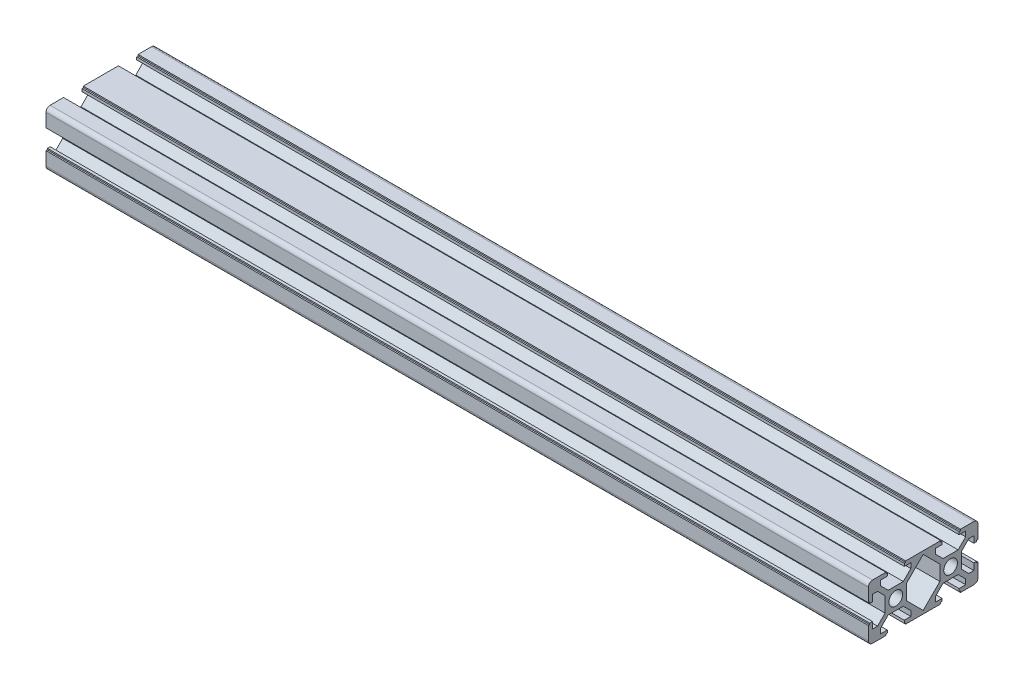
SolidWorks part; units mm, degrees
ref_plane "前视基准面" through (0, 0, 0) normal (0, 0, 1) x (1, 0, 0)
ref_plane "上视基准面" through (0, 0, 0) normal (0, 1, 0) x (1, 0, 0)
ref_plane "右视基准面" through (0, 0, 0) normal (1, 0, 0) x (0, 0, -1)
sketch "草图1" plane through (0, 0, 0) normal (0, 0, 1) x (1, 0, 0)
  line L0 (-53.3425, -1.4522) -> (246.6575, -1.4522)
other "铝型材 20X40XR1.5(2)"
ref_plane "基准面9" through (-53.3425, -1.4522, 0) normal (1, 0, 0) x (0, 1, 0)
sketch "Sketch16" plane through (-53.3425, -1.4522, 0) normal (1, 0, 0) x (0, 1, 0)
  line L0 (-3.6, 10) -> (-3.6, 9.5)
  line L1 (-3.6, 9.5) -> (-3.1, 9.5)
  line L2 (-3.1, 9.5) -> (-3.1, 8.5)
  line L3 (-3.1, 8.5) -> (-5.5, 8.5)
  line L4 (8.85, -10) -> (2.75, -3.9)
  line L5 (-10, -16.4) -> (-10, -3.6)
  line L6 (8.5, 10) -> (3.6, 10)
  line L7 (10, 8.5) -> (10, 3.6)
  line L8 (0, 14.8756) -> (0, 0) construction
  line L9 (0, 0) -> (10, 0) construction
  line L10 (-5.5, 8.5) -> (-5.5, 6.65)
  line L11 (-5.5, 6.65) -> (-2.75, 3.9)
  line L12 (-2.75, 3.9) -> (2.75, 3.9)
  line L13 (5.5, 6.65) -> (2.75, 3.9)
  line L14 (5.5, 8.5) -> (5.5, 6.65)
  line L15 (3.1, 8.5) -> (5.5, 8.5)
  line L16 (3.1, 9.5) -> (3.1, 8.5)
  line L17 (3.6, 9.5) -> (3.1, 9.5)
  line L18 (3.6, 10) -> (3.6, 9.5)
  line L19 (-3.6, 10) -> (-8.5, 10)
  line L20 (10, 3.6) -> (9.5, 3.6)
  line L21 (9.5, 3.6) -> (9.5, 3.1)
  line L22 (9.5, 3.1) -> (8.5, 3.1)
  line L23 (8.5, 3.1) -> (8.5, 5.5)
  line L24 (8.5, 5.5) -> (6.65, 5.5)
  line L25 (6.65, 5.5) -> (3.9, 2.75)
  line L26 (3.9, 2.75) -> (3.9, -2.75)
  line L27 (6.65, -5.5) -> (3.9, -2.75)
  line L28 (8.5, -5.5) -> (6.65, -5.5)
  line L29 (8.5, -3.1) -> (8.5, -5.5)
  line L30 (9.5, -3.1) -> (8.5, -3.1)
  line L31 (9.5, -3.6) -> (9.5, -3.1)
  line L32 (10, -3.6) -> (9.5, -3.6)
  line L33 (8.85, -10) -> (2.75, -16.1)
  line L34 (-8.85, -10) -> (-2.75, -16.1)
  line L35 (-8.85, -10) -> (-2.75, -3.9)
  line L39 (2.75, -3.9) -> (-2.75, -3.9)
  line L46 (-10, -3.6) -> (-9.5, -3.6)
  line L47 (-9.5, -3.6) -> (-9.5, -3.1)
  line L48 (-9.5, -3.1) -> (-8.5, -3.1)
  line L49 (-8.5, -3.1) -> (-8.5, -5.5)
  line L50 (-8.5, -5.5) -> (-6.65, -5.5)
  line L51 (-6.65, -5.5) -> (-3.9, -2.75)
  line L52 (-3.9, -2.75) -> (-3.9, 2.75)
  line L53 (-6.65, 5.5) -> (-3.9, 2.75)
  line L54 (-8.5, 5.5) -> (-6.65, 5.5)
  line L55 (-8.5, 3.1) -> (-8.5, 5.5)
  line L56 (-9.5, 3.1) -> (-8.5, 3.1)
  line L57 (-9.5, 3.6) -> (-9.5, 3.1)
  line L58 (-10, 3.6) -> (-9.5, 3.6)
  line L60 (-10, 3.6) -> (-10, 8.5)
  line L61 (10, -3.6) -> (10, -16.4)
  line L66 (-8.5, -30) -> (-3.6, -30)
  line L67 (-10, -28.5) -> (-10, -23.6)
  line L72 (-2.75, -16.1) -> (2.75, -16.1)
  line L80 (10, -16.4) -> (9.5, -16.4)
  line L81 (9.5, -16.4) -> (9.5, -16.9)
  line L82 (9.5, -16.9) -> (8.5, -16.9)
  line L83 (8.5, -16.9) -> (8.5, -14.5)
  line L84 (8.5, -14.5) -> (6.65, -14.5)
  line L85 (6.65, -14.5) -> (3.9, -17.25)
  line L86 (3.9, -17.25) -> (3.9, -22.75)
  line L87 (6.65, -25.5) -> (3.9, -22.75)
  line L88 (8.5, -25.5) -> (6.65, -25.5)
  line L89 (8.5, -23.1) -> (8.5, -25.5)
  line L90 (9.5, -23.1) -> (8.5, -23.1)
  line L91 (9.5, -23.6) -> (9.5, -23.1)
  line L92 (10, -23.6) -> (9.5, -23.6)
  line L93 (3.6, -30) -> (3.6, -29.5)
  line L94 (3.6, -29.5) -> (3.1, -29.5)
  line L95 (3.1, -29.5) -> (3.1, -28.5)
  line L96 (3.1, -28.5) -> (5.5, -28.5)
  line L97 (5.5, -28.5) -> (5.5, -26.65)
  line L98 (5.5, -26.65) -> (2.75, -23.9)
  line L99 (2.75, -23.9) -> (-2.75, -23.9)
  line L100 (-5.5, -26.65) -> (-2.75, -23.9)
  line L101 (-5.5, -28.5) -> (-5.5, -26.65)
  line L102 (-3.1, -28.5) -> (-5.5, -28.5)
  line L103 (-3.1, -29.5) -> (-3.1, -28.5)
  line L104 (-3.6, -29.5) -> (-3.1, -29.5)
  line L105 (-3.6, -30) -> (-3.6, -29.5)
  line L106 (-10, -23.6) -> (-9.5, -23.6)
  line L107 (-9.5, -23.6) -> (-9.5, -23.1)
  line L108 (-9.5, -23.1) -> (-8.5, -23.1)
  line L109 (-8.5, -23.1) -> (-8.5, -25.5)
  line L110 (-8.5, -25.5) -> (-6.65, -25.5)
  line L111 (-6.65, -25.5) -> (-3.9, -22.75)
  line L112 (-3.9, -22.75) -> (-3.9, -17.25)
  line L113 (-6.65, -14.5) -> (-3.9, -17.25)
  line L114 (-8.5, -14.5) -> (-6.65, -14.5)
  line L115 (-8.5, -16.9) -> (-8.5, -14.5)
  line L116 (-9.5, -16.9) -> (-8.5, -16.9)
  line L117 (-9.5, -16.4) -> (-9.5, -16.9)
  line L118 (-10, -16.4) -> (-9.5, -16.4)
  line L119 (3.6, -30) -> (8.5, -30)
  line L121 (10, -23.6) -> (10, -28.5)
  line L122 (0, -20) -> (10, -20) construction
  line L125 (3.6, -10) -> (3.6, -9.5) [skipped]
  line L127 (3.6, -9.5) -> (3.1, -9.5) [skipped]
  line L129 (3.1, -9.5) -> (3.1, -8.5) [skipped]
  line L131 (3.1, -8.5) -> (5.5, -8.5) [skipped]
  line L133 (-3.1, -8.5) -> (-5.5, -8.5) [skipped]
  line L135 (-3.1, -9.5) -> (-3.1, -8.5) [skipped]
  line L137 (-3.6, -9.5) -> (-3.1, -9.5) [skipped]
  line L139 (-3.6, -10) -> (-3.6, -9.5) [skipped]
  line L141 (-3.6, -10) -> (-3.6, -10.5) [skipped]
  line L142 (-3.6, -10.5) -> (-3.1, -10.5) [skipped]
  line L143 (-3.1, -10.5) -> (-3.1, -11.5) [skipped]
  line L144 (-3.1, -11.5) -> (-5.5, -11.5) [skipped]
  line L145 (8.5, -10) -> (3.6, -10) [skipped]
  line L146 (3.1, -11.5) -> (5.5, -11.5) [skipped]
  line L147 (3.1, -10.5) -> (3.1, -11.5) [skipped]
  line L148 (3.6, -10.5) -> (3.1, -10.5) [skipped]
  line L149 (3.6, -10) -> (3.6, -10.5) [skipped]
  line L150 (-3.6, -10) -> (-8.5, -10) [skipped]
  line L151 (-10, -16.4) -> (-10, -11.5) [skipped]
  line L152 (10, -11.5) -> (10, -16.4) [skipped]
  line L154 (-5.5, -8.5) -> (-5.5, -6.65) [skipped]
  line L156 (5.5, -8.5) -> (5.5, -6.65) [skipped]
  line L157 (5.5, -11.5) -> (5.5, -13.35) [skipped]
  line L158 (-5.5, -11.5) -> (-5.5, -13.35) [skipped]
  line L160 (-12.2446, -13.3946) -> (-10, -11.15) [skipped]
  line L161 (13.644, -5.206) -> (10, -8.85) [skipped]
  line L163 (12.1963, -13.3463) -> (10, -11.15) [skipped]
  line L164 (-11.1344, -7.7156) -> (-10, -8.85) [skipped]
  circle A0 centre (0, 0) radius 2.5
  arc A1 (-10, 8.5) -> (-8.5, 10) centre (-8.5, 8.5) cw
  arc A2 (10, 8.5) -> (8.5, 10) centre (8.5, 8.5) ccw
  arc A3 (10, -28.5) -> (8.5, -30) centre (8.5, -28.5) cw
  arc A4 (-10, -28.5) -> (-8.5, -30) centre (-8.5, -28.5) ccw
  circle A5 centre (0, -20) radius 2.5
  arc A12 (-10, -11.5) -> (-8.5, -10) centre (-8.5, -11.5) cw [skipped]
  arc A13 (10, -11.5) -> (8.5, -10) centre (8.5, -11.5) ccw [skipped]
  point P0 (-10, 0)
  point P1 (10, 0)
  point P2 (0, 10)
  point P4 (0, 0)
  point P5 (0, -10)
  point P6 (-10, -10)
  point P7 (10, 10)
  point P8 (-10, 10)
  point P12 (-10, -10)
  point P13 (10, -10)
  point P15 (0, -10)
  point P16 (10, -10)
  point P36 (-10, 10)
  point P39 (10, 10)
  point P43 (-10, -20)
  point P44 (10, -20)
  point P62 (0, 0)
  point P88 (0, -30)
  point P89 (0, -20)
  point P90 (-10, -30)
  point P91 (10, -30)
  dimension "D1" = 11
  dimension "D2" = 20
  dimension "D3" = 6.2
  dimension "D4" = 7.2
  dimension "D5" = 6.1
  dimension "D6" = 5
  dimension "D7" = 1.5
  dimension "D8" = 45
  dimension "D14" = 20
  dimension "D15" = 1.5
  dimension "D9" = 0.5
  dimension "D10" = 1
  dimension "D11" = 5.5
  dimension "D12" = 10
  dimension "D13" = 40
  dimension "D16" = 45
  dimension "D17" = 45
  dimension "D18" = 45
  dimension "D19" = 6.2
